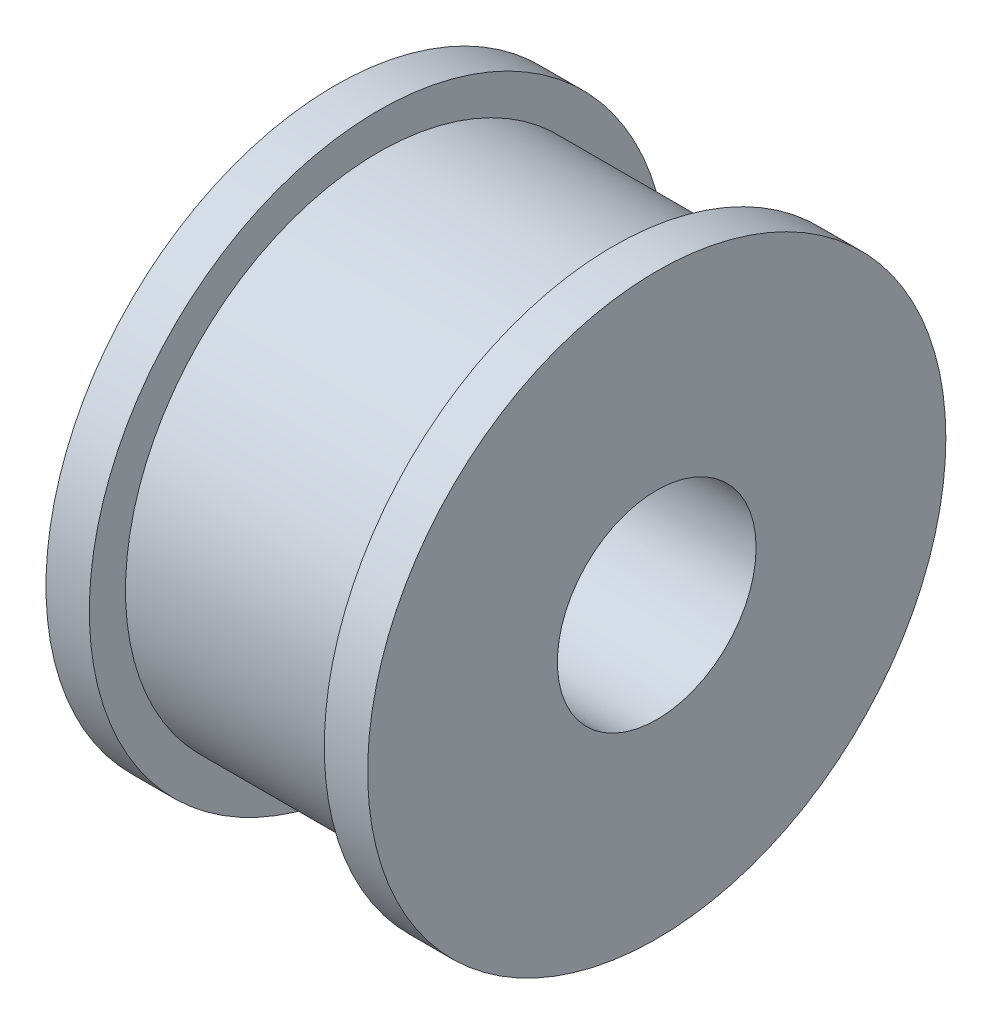
SolidWorks part; units mm, degrees
ref_plane "Plan de face" through (0, 0, 0) normal (0, 0, 1) x (1, 0, 0)
ref_plane "Plan de dessus" through (0, 0, 0) normal (0, 1, 0) x (1, 0, 0)
ref_plane "Plan de droite" through (0, 0, 0) normal (1, 0, 0) x (0, 0, -1)
sketch "Esquisse1" plane through (0, 0, 0) normal (0, 1, 0) x (1, 0, 0)
  line L0 (44.5, 0) -> (-44.5, 0)
  line L1 (-44.5, 0) -> (-44.5, 80)
  line L2 (-44.5, 80) -> (-32.5, 80)
  line L3 (-32.5, 80) -> (-32.5, 70)
  line L4 (-32.5, 70) -> (32.5, 70)
  line L5 (0, 164.245) -> (0, 2.8356) construction
  line L6 (32.5, 80) -> (32.5, 70)
  line L7 (44.5, 80) -> (32.5, 80)
  line L8 (44.5, 0) -> (44.5, 80)
  point P10 (0, 70)
  point P13 (0, 0)
  dimension "D1" = 65
  dimension "D2" = 89
  dimension "D3" = 80
  dimension "D4" = 10
revolve "Révolution2" add sketch "Esquisse1" angle 360 about L0
sketch "Esquisse2" plane through (0, 0, 0) normal (1, 0, 0) x (0, 0, -1)
  circle A0 centre (0, 0) radius 27.5
  dimension "D1" = 55
extrude "Enlèv. mat.-Extru.1" cut sketch "Esquisse2" against normal mid plane 110
